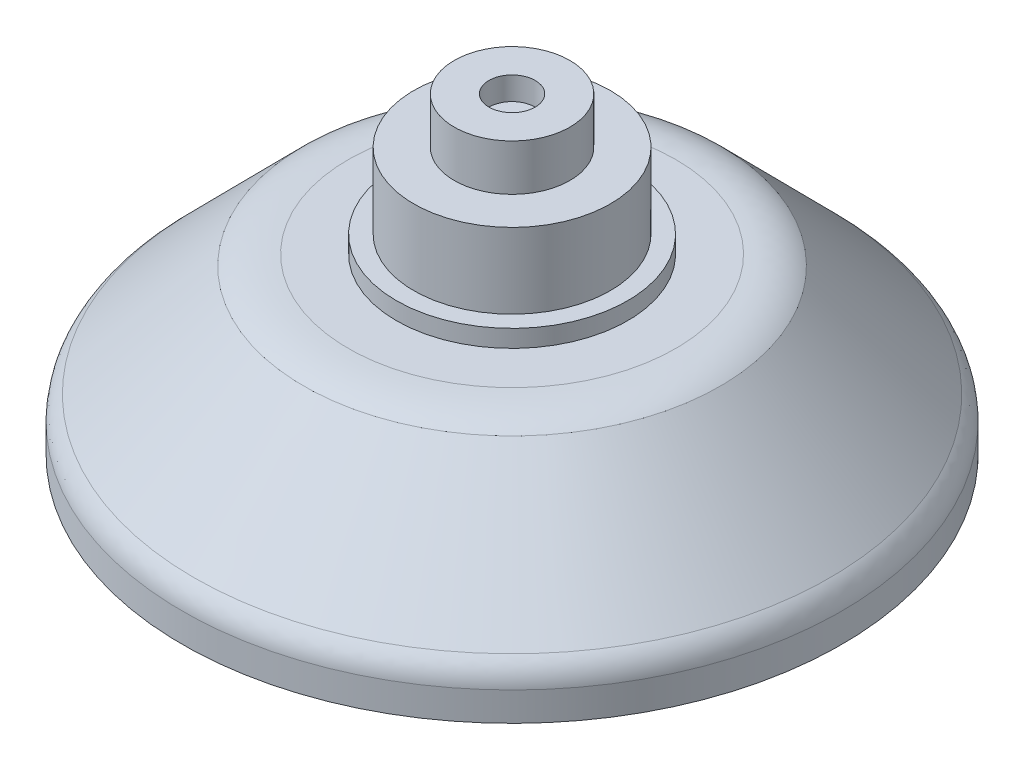
SolidWorks part; units mm, degrees
material "1.4511 (X3CrNb17)"
ref_plane "前视基准面" through (0, 0, 0) normal (0, 0, 1) x (1, 0, 0)
ref_plane "上视基准面" through (0, 0, 0) normal (0, 1, 0) x (1, 0, 0)
ref_plane "右视基准面" through (0, 0, 0) normal (1, 0, 0) x (0, 0, -1)
sketch "草图1" plane through (0, 0, 0) normal (0, 0, 1) x (1, 0, 0)
  line L0 (0, 0) -> (28.5, 0)
  line L2 (0, 2.0065) -> (27.5, 2.0065)
  line L4 (0, 0) -> (0, 24.5)
  line L5 (0, 11.6) -> (18, 11.6)
  line L6 (27.5, 2.0065) -> (18, 11.6)
  line L7 (0, 12.5) -> (14.1563, 12.5)
  line L8 (10, 12.5) -> (10, 14)
  line L9 (10, 14) -> (0, 14)
  line L10 (8.5, 14) -> (8.5, 20.5)
  line L11 (8.5, 20.5) -> (0, 20.5)
  line L12 (5, 20.5) -> (5, 24.5)
  line L13 (0, 24.5) -> (5, 24.5)
  spline S0 degree 2 poles (28.5, 0) (28.4188, 1.212) (27.5, 2.0065) knots 0 0 0 1 1 1
  spline S1 degree 3 poles (18, 11.6) (16.7976, 12.3644) (15.5208, 12.5) (14.1563, 12.5) knots 0 0 0 0 1 1 1 1
  dimension "D1" = 24.5
  dimension "D2" = 28.5
  dimension "D3" = 27.5
  dimension "D4" = 18
revolve "旋转1" add sketch "草图1" angle 360 about L4
sketch "草图2" plane through (0, 0, 0) normal (0, -1, 0) x (1, 0, 0)
  circle A0 centre (0, 0) radius 28.5
extrude "凸台-拉伸1" add sketch "草图2" along normal blind 2.5
sketch "草图3" plane through (0, 24.5, 0) normal (0, 1, 0) x (1, 0, 0)
  circle A0 centre (0, 0) radius 2
extrude "切除-拉伸1" cut sketch "草图3" against normal blind 2
